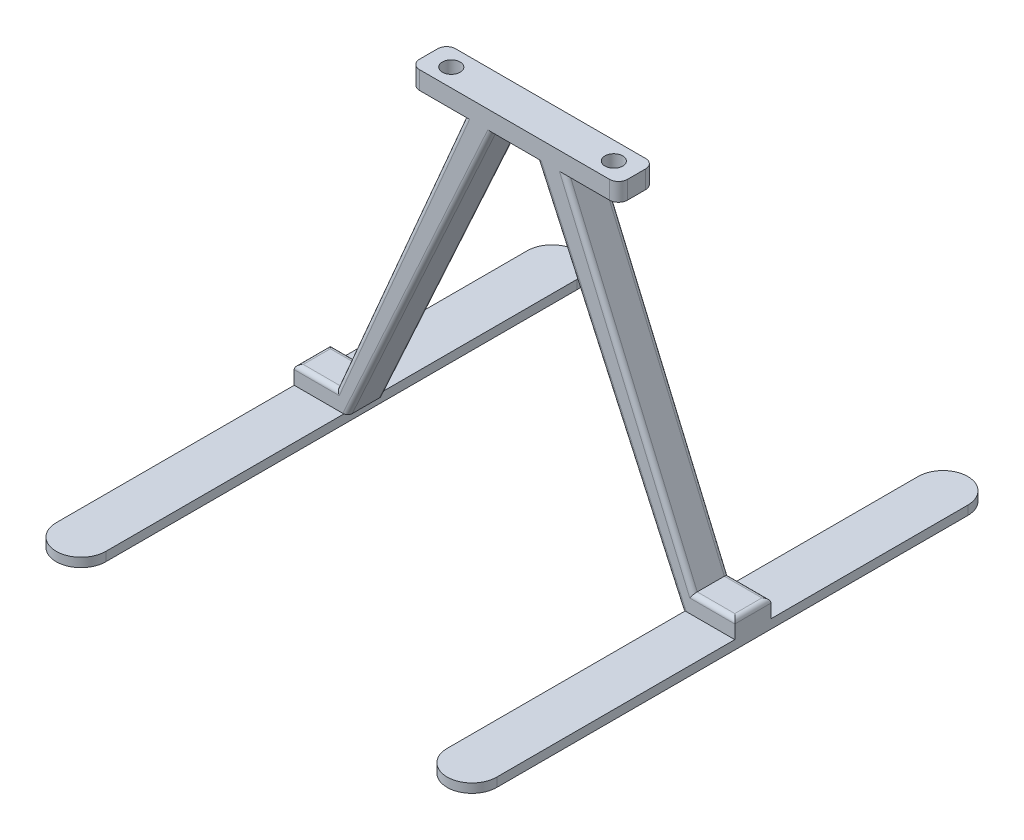
SolidWorks part; units mm, degrees
ref_plane "Front Plane" through (0, 0, 0) normal (0, 0, 1) x (1, 0, 0)
ref_plane "Top Plane" through (0, 0, 0) normal (0, 1, 0) x (1, 0, 0)
ref_plane "Right Plane" through (0, 0, 0) normal (1, 0, 0) x (0, 0, -1)
sketch "Sketch1" plane through (0, 0, 0) normal (0, 1, 0) x (1, 0, 0)
  line L0 (0, 0) -> (-22.86, 0) construction
  line L1 (0, 0) -> (0, 17.5181) construction
  line L2 (26.7058, 5.08) -> (-26.7058, 5.08)
  line L3 (-29.2458, 2.54) -> (-29.2458, -2.54)
  line L4 (-26.7058, -5.08) -> (26.7058, -5.08)
  line L5 (29.2458, 2.54) -> (29.2458, -2.54)
  circle A0 centre (-22.86, 0) radius 2.5
  circle A1 centre (22.86, 0) radius 2.5
  arc A2 (26.7058, 5.08) -> (29.2458, 2.54) centre (26.7058, 2.54) cw
  arc A3 (29.2458, -2.54) -> (26.7058, -5.08) centre (26.7058, -2.54) cw
  arc A4 (-29.2458, -2.54) -> (-26.7058, -5.08) centre (-26.7058, -2.54) ccw
  arc A5 (-29.2458, 2.54) -> (-26.7058, 5.08) centre (-26.7058, 2.54) cw
  point P12 (0, -5.08)
  point P13 (0, 5.08)
  point P15 (29.2458, 5.08)
  point P18 (29.2458, -5.08)
  point P21 (-29.2458, -5.08)
  point P24 (-29.2458, 5.08)
  dimension "D2" = 5
  dimension "D3" = 5.08
  dimension "D5" = 2.54
  dimension "D1" = 22.86
  dimension "D4" = 5.08
extrude "Boss-Extrude1" add sketch "Sketch1" along normal blind 5.08
sketch "Sketch2" plane through (0, 0, 5.08) normal (0, 0, 1) x (1, 0, 0)
  line L0 (-14.0071, 0) -> (-50.125, -84.328)
  line L1 (-26.7058, 0) -> (26.7058, 0) construction
  line L2 (-14.0071, 0) -> (-6.1223, 0)
  line L3 (-6.1223, 0) -> (-46.8928, -89.408)
  line L4 (0, 0) -> (0, -89.408) construction
  line L5 (0, -89.408) -> (-50.8, -89.408) construction
  line L6 (50.8, -89.408) -> (61.9471, -89.408)
  line L7 (-50.8, -89.408) -> (-61.9471, -89.408)
  line L9 (-50.125, -84.328) -> (-61.9471, -84.328)
  line L10 (-61.9471, -89.408) -> (-61.9471, -84.328)
  line L11 (61.9471, -89.408) -> (61.9471, -84.328)
  line L12 (50.125, -84.328) -> (61.9471, -84.328)
  line L13 (14.0071, 0) -> (50.125, -84.328)
  line L14 (14.0071, 0) -> (6.1223, 0)
  line L15 (6.1223, 0) -> (46.8928, -89.408)
  line L17 (-46.8928, -89.408) -> (-50.8, -89.408)
  line L18 (46.8928, -89.408) -> (50.8, -89.408)
  dimension "D1" = 89.408
  dimension "D2" = 50.8
  dimension "D3" = 5.08
extrude "Boss-Extrude2" add sketch "Sketch2" against normal blind 10.16
fillet "Fillet2" radius 1.27 6 edges at (56.036, -84.328, 5.08) (56.036, -84.328, -5.08) (61.9471, -84.328, 0) (-56.036, -84.328, 5.08) (-56.036, -84.328, -5.08) (-61.9471, -84.328, 0)
fillet "Fillet3" radius 1.27 8 edges at (32.338, -42.799, 5.08) (26.5076, -44.704, 5.08) (26.5076, -44.704, -5.08) (32.338, -42.799, -5.08) (-26.5076, -44.704, 5.08) (-26.5076, -44.704, -5.08) (-32.338, -42.799, -5.08) (-32.338, -42.799, 5.08)
sketch "Sketch3" plane through (0, -89.408, 0) normal (0, -1, 0) x (1, 0, 0)
  line L0 (0, 0) -> (0, 54.3232) construction
  line L1 (47.9875, 72.0059) -> (47.9875, -60.441)
  line L2 (61.9471, 72.0059) -> (61.9471, -60.441)
  line L3 (-61.9471, 72.0059) -> (-61.9471, -60.441)
  line L4 (-47.9875, 72.0059) -> (-47.9875, -60.441)
  arc A0 (-61.9471, 72.0059) -> (-47.9875, 72.0059) centre (-54.9673, 72.0059) cw
  arc A1 (-47.9875, -60.441) -> (-61.9471, -60.441) centre (-54.9673, -60.441) cw
  arc A2 (47.9875, -60.441) -> (61.9471, -60.441) centre (54.9673, -60.441) ccw
  arc A3 (61.9471, 72.0059) -> (47.9875, 72.0059) centre (54.9673, 72.0059) ccw
extrude "Boss-Extrude3" add sketch "Sketch3" along normal blind 2.54
